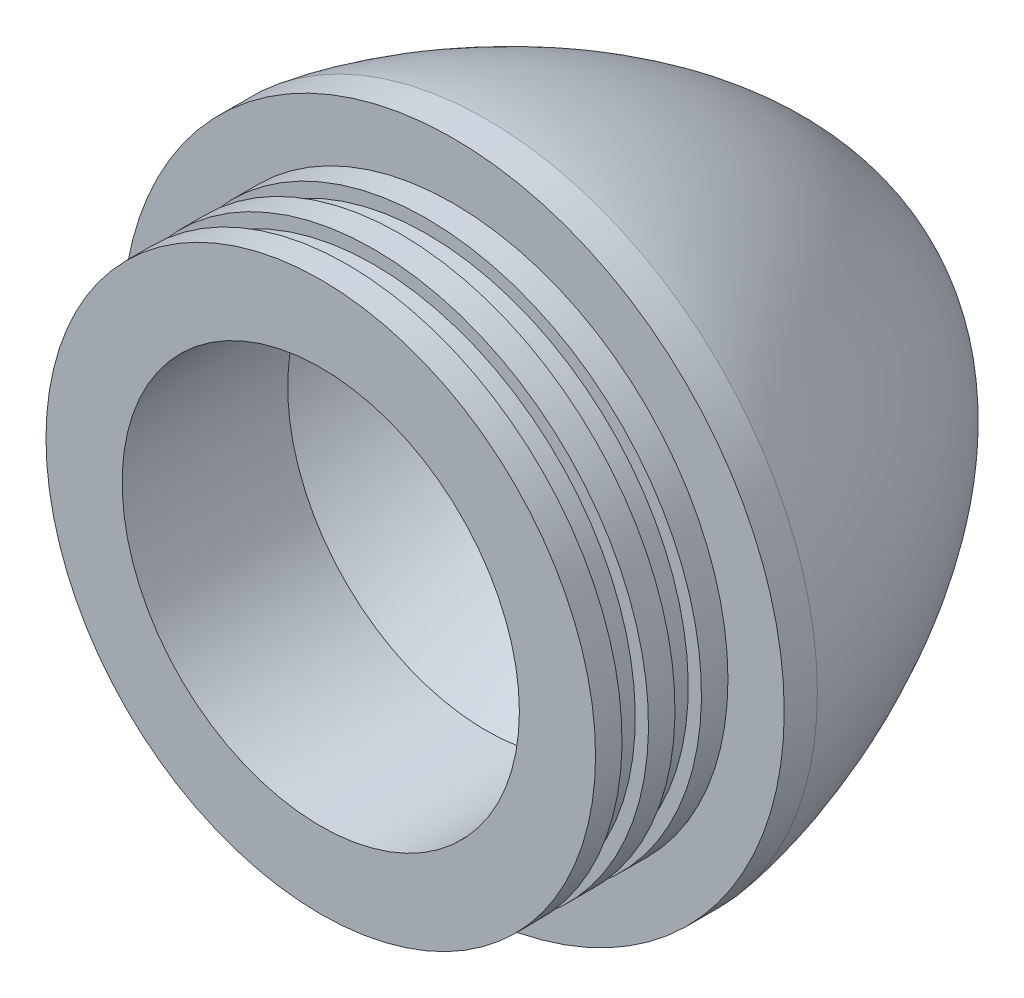
SolidWorks part; units mm, degrees
ref_plane "Front Plane" through (0, 0, 0) normal (0, 0, 1) x (1, 0, 0)
ref_plane "Top Plane" through (0, 0, 0) normal (0, 1, 0) x (1, 0, 0)
ref_plane "Right Plane" through (0, 0, 0) normal (1, 0, 0) x (0, 0, -1)
sketch "Sketch1" plane through (0, 0, 0) normal (0, 0, 1) x (1, 0, 0)
  circle A0 centre (0, 0) radius 50
  dimension "D1" = 100
extrude "Boss-Extrude1" add sketch "Sketch1" along normal blind 5
sketch "Sketch2" plane through (0, 0, 5) normal (0, 0, 1) x (1, 0, 0)
  circle A0 centre (0, 0) radius 41.5
  dimension "D1" = 83
extrude "Boss-Extrude2" add sketch "Sketch2" along normal blind 20
sketch "Sketch4" plane through (0, 0, 0) normal (1, 0, 0) x (0, 0, -1)
  line L0 (-5, 41.5) -> (-25, 41.5) construction
  line L5 (-13, 41.5) -> (-9, 41.5)
  line L6 (-13, 41.5) -> (-13, 39.5)
  line L7 (-13, 39.5) -> (-9, 39.5)
  line L8 (-9, 41.5) -> (-9, 39.5)
  line L9 (-21, 41.5) -> (-21, 39.5)
  line L10 (-5, 41.5) -> (-5, -41.5) construction
  line L11 (0, 0) -> (-33.7056, 0) construction
  line L12 (-21, 39.5) -> (-17, 39.5)
  line L13 (-17, 41.5) -> (-17, 39.5)
  line L14 (-21, 41.5) -> (-17, 41.5)
  point P8 (-9, 40.5)
  dimension "D1" = 4
  dimension "D2" = 4
  dimension "D3" = 2
  dimension "D4" = 4
revolve "Cut-Revolve1" cut sketch "Sketch4" angle 360 about L11
sketch "Sketch6" plane through (0, 0, 25) normal (0, 0, 1) x (1, 0, 0)
  circle A0 centre (0, 0) radius 30
  dimension "D1" = 60
extrude "Cut-Extrude1" cut sketch "Sketch6" against normal through all
sketch "Sketch5" plane through (0, 0, 0) normal (1, 0, 0) x (0, 0, -1)
  line L0 (0, 0) -> (60, 0) construction
  line L1 (0, -50) -> (0, 50) construction
  line L3 (-85.4156, -61.2452) -> (84.1215, -38.9252) construction
  line L4 (60, -118.5) -> (60, 118.5) construction
  line L5 (60, 0) -> (57, 0)
  line L7 (0, -50) -> (0, -46.9722)
  spline S0 degree 3 poles (60, 0) (60, -30) (18.3417, -47.5853) (0, -50) knots 0 0 0 0 1 1 1 1
  spline S1 degree 1 poles (57, 0) (-0.3916, -47.0257) knots 0 0 1 1 construction
  spline S2 degree 3 poles (57, 0) (57, -0.8395) (56.9262, -2.5327) (56.4986, -5.7873) (55.4644, -9.7108) (53.4928, -14.1836) (49.9782, -19.8481) (44.1032, -26.3376) (35.37, -33.0451) (27.3285, -37.6404) (20.8297, -40.6816) (16.0222, -42.6375) (11.3816, -44.2613) (7.7384, -45.3327) (5.0118, -46.018) (3.0737, -46.4457) (1.5636, -46.7293) (0.5912, -46.8857) (0.141, -46.9523) (-0.1325, -46.991) (-0.2924, -47.0126) (-0.3916, -47.0257) knots 0 0 0 0 0.03125 0.0625 0.125 0.1875 0.25 0.375 0.5 0.625 0.6875 0.75 0.8125 0.875 0.90625 0.9375 0.96875 0.984375 0.990544 0.994327 1 1 1 1
  dimension "D1" = 60
  dimension "D2" = 90
  dimension "D3" = 55.5
  dimension "D4" = 82.5
  dimension "D5" = 90
  dimension "D6" = 3
revolve "Revolve2" add sketch "Sketch5" angle 360 about L0
